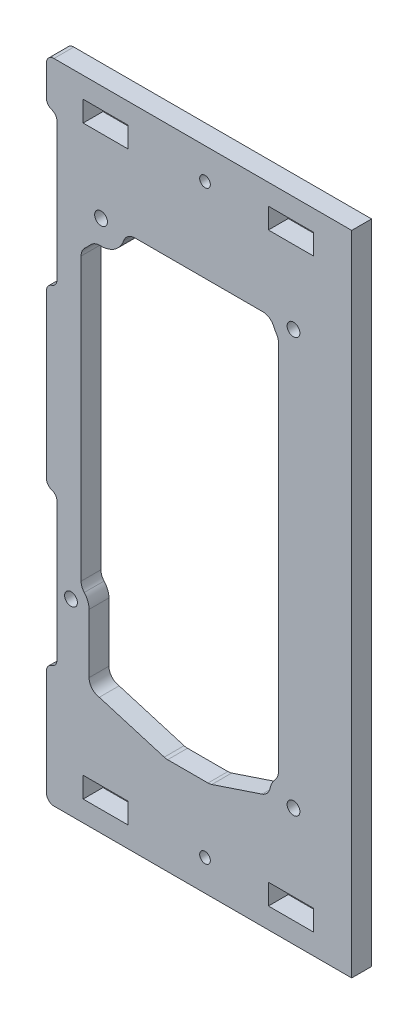
SolidWorks part; units mm, degrees
ref_plane "Front Plane" through (0, 0, 0) normal (0, 0, 1) x (1, 0, 0)
ref_plane "Top Plane" through (0, 0, 0) normal (0, 1, 0) x (1, 0, 0)
ref_plane "Right Plane" through (0, 0, 0) normal (1, 0, 0) x (0, 0, -1)
sketch "Model" plane through (0, 0, 0) normal (0, 0, 1) x (1, 0, 0)
  line L0 (-44.84, -45.4) -> (-44.84, -65.0458)
  line L1 (-19.8446, -75.4415) -> (-41.4437, -69)
  line L2 (-5.2865, -75.6083) -> (-18.7014, -75.6083)
  line L3 (12.6879, -69.823) -> (-4.0195, -75.4023)
  line L4 (18.1422, -60.6627) -> (18.1422, 62.8754)
  line L5 (12.8952, 69.2) -> (-29.5441, 69.2)
  line L6 (-44.1353, 60.0368) -> (-46.3284, 57.8437)
  line L7 (-47.5, -38.6085) -> (-47.5, 55.0153)
  line L8 (-46.81, 100.53) -> (-46.81, 93.67)
  line L9 (-46.81, 93.67) -> (-31.81, 93.67)
  line L10 (-31.81, 93.67) -> (-31.81, 100.53)
  line L11 (-31.81, 100.53) -> (-46.81, 100.53)
  line L12 (14.79, 100.53) -> (14.79, 93.67)
  line L13 (14.79, 93.67) -> (29.79, 93.67)
  line L14 (29.79, 93.67) -> (29.79, 100.53)
  line L15 (29.79, 100.53) -> (14.79, 100.53)
  line L16 (-46.81, -94.13) -> (-46.81, -100.99)
  line L17 (-46.81, -100.99) -> (-31.81, -100.99)
  line L18 (-31.81, -100.99) -> (-31.81, -94.13)
  line L19 (-31.81, -94.13) -> (-46.81, -94.13)
  line L20 (14.79, -94.13) -> (14.79, -100.99)
  line L21 (14.79, -100.99) -> (29.79, -100.99)
  line L22 (29.79, -100.99) -> (29.79, -94.13)
  line L23 (29.79, -94.13) -> (14.79, -94.13)
  line L24 (-55.51, -65.37) -> (-55.51, -19.57)
  line L25 (-59.01, -14.8003) -> (-59.01, 39.3403)
  line L26 (-55.51, 44.11) -> (-55.51, 89.91)
  line L27 (-59.01, 94.6797) -> (-59.01, 104.91)
  line L28 (42.49, 107.41) -> (-56.51, 107.41)
  line L29 (42.49, 107.41) -> (42.49, -107.87)
  line L30 (42.49, -107.87) -> (-56.51, -107.87)
  line L31 (-59.01, -105.37) -> (-59.01, -70.1397)
  circle A0 centre (-50.84, -45.4) radius 2.125
  circle A1 centre (23.1422, 69.2) radius 2.125
  circle A2 centre (-40.8578, 69.2) radius 2.125
  circle A3 centre (23.1422, -68.6) radius 2.125
  circle A4 centre (-6.285, -97.56) radius 1.775
  circle A5 centre (-6.285, 97.1) radius 1.775
  arc A6 (-44.84, -65.0458) -> (-41.4437, -69) centre (-40.84, -65.0458) ccw
  arc A7 (-19.8446, -75.4415) -> (-18.7014, -75.6083) centre (-18.7014, -71.6083) ccw
  arc A8 (-5.2865, -75.6083) -> (-4.0195, -75.4023) centre (-5.2865, -71.6083) ccw
  arc A9 (12.6879, -69.823) -> (15.328, -66.8859) centre (11.4209, -66.0289) ccw
  arc A10 (17.1422, -63.3085) -> (15.328, -66.8859) centre (23.1422, -68.6) ccw
  arc A11 (17.1422, -63.3085) -> (18.1422, -60.6627) centre (14.1422, -60.6627) ccw
  arc A12 (18.1422, 62.8754) -> (17.4149, 65.1753) centre (14.1422, 62.8754) ccw
  arc A13 (16.6214, 66.6545) -> (17.4149, 65.1753) centre (23.1422, 69.2) ccw
  arc A14 (16.6214, 66.6545) -> (12.8952, 69.2) centre (12.8952, 65.2) ccw
  arc A15 (-29.5441, 69.2) -> (-33.3153, 66.5333) centre (-29.5441, 65.2) ccw
  arc A16 (-41.1572, 61.2056) -> (-33.3153, 66.5333) centre (-40.8578, 69.2) ccw
  arc A17 (-41.1572, 61.2056) -> (-44.1353, 60.0368) centre (-41.3069, 57.2084) ccw
  arc A18 (-46.3284, 57.8437) -> (-47.5, 55.0153) centre (-43.5, 55.0153) ccw
  arc A19 (-47.5, -38.6085) -> (-46.436, -41.3251) centre (-43.5, -38.6085) ccw
  arc A20 (-44.84, -45.4) -> (-46.436, -41.3251) centre (-50.84, -45.4) ccw
  arc A21 (-57.26, -67.7548) -> (-59.01, -70.1397) centre (-56.51, -70.1397) ccw
  arc A22 (-57.26, -67.7548) -> (-55.51, -65.37) centre (-58.01, -65.37) ccw
  arc A23 (-55.51, -19.57) -> (-57.26, -17.1852) centre (-58.01, -19.57) ccw
  arc A24 (-59.01, -14.8003) -> (-57.26, -17.1852) centre (-56.51, -14.8003) ccw
  arc A25 (-57.26, 41.7252) -> (-59.01, 39.3403) centre (-56.51, 39.3403) ccw
  arc A26 (-57.26, 41.7252) -> (-55.51, 44.11) centre (-58.01, 44.11) ccw
  arc A27 (-55.51, 89.91) -> (-57.26, 92.2948) centre (-58.01, 89.91) ccw
  arc A28 (-59.01, 94.6797) -> (-57.26, 92.2948) centre (-56.51, 94.6797) ccw
  arc A29 (-56.51, 107.41) -> (-59.01, 104.91) centre (-56.51, 104.91) ccw
  arc A30 (-59.01, -105.37) -> (-56.51, -107.87) centre (-56.51, -105.37) ccw
extrude "Boss-Extrude1" add sketch "Model" along normal blind 6.6
